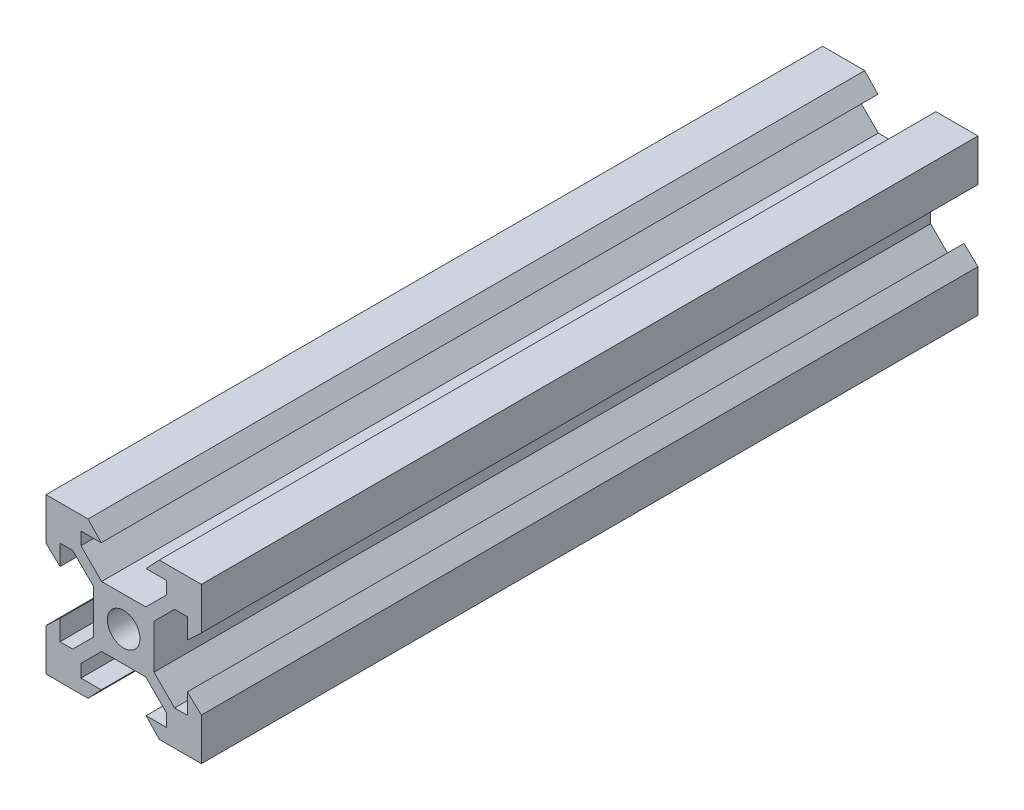
SolidWorks part; units mm, degrees
ref_plane "Front Plane" through (0, 0, 0) normal (0, 0, 1) x (1, 0, 0)
ref_plane "Top Plane" through (0, 0, 0) normal (0, 1, 0) x (1, 0, 0)
ref_plane "Right Plane" through (0, 0, 0) normal (1, 0, 0) x (0, 0, -1)
sketch "Sketch1" plane through (0, 0, 0) normal (0, 0, 1) x (1, 0, 0)
  line L0 (-4.58, 10) -> (-2.885, 8.2)
  line L1 (10, -10) -> (4.58, -10)
  line L2 (10, -10) -> (10, -4.58)
  line L3 (10, 10) -> (4.58, 10)
  line L4 (-10, -10) -> (-10, -4.58)
  line L5 (10, -10) -> (-10, 10) construction
  line L6 (10, 10) -> (-10, -10) construction
  line L7 (-2.8393, 3.9) -> (2.8393, 3.9)
  line L8 (-3.9, 2.8393) -> (-3.9, -2.8393)
  line L9 (-2.8393, -3.9) -> (2.8393, -3.9)
  line L10 (3.9, 2.8393) -> (3.9, -2.8393)
  line L11 (-3.9, 3.9) -> (3.9, -3.9) construction
  line L12 (-3.9, -3.9) -> (3.9, 3.9) construction
  line L13 (4.58, 10) -> (2.885, 8.2)
  line L14 (10, 4.58) -> (10, 10)
  line L15 (-5.5, 8.2) -> (-2.885, 8.2)
  line L16 (-8.2, 5.5) -> (-8.2, 2.885)
  line L17 (-5.5, -8.2) -> (-2.885, -8.2)
  line L18 (8.2, 5.5) -> (8.2, 2.885)
  line L19 (-8.2, 8.2) -> (8.2, -8.2) construction
  line L20 (-8.2, -8.2) -> (8.2, 8.2) construction
  line L21 (10, 4.58) -> (8.2, 2.885)
  line L22 (10, -4.58) -> (8.2, -2.885)
  line L23 (4.58, -10) -> (2.885, -8.2)
  line L24 (-4.58, -10) -> (-2.885, -8.2)
  line L25 (-10, -4.58) -> (-8.2, -2.885)
  line L26 (-10, 4.58) -> (-8.2, 2.885)
  line L27 (0, 14.7958) -> (0, -12.2524) construction
  line L28 (-5.5, 8.2) -> (-5.5, 6.5607)
  line L29 (5.5, 8.2) -> (5.5, 6.5607)
  line L30 (-5.5, 6.5607) -> (-2.8393, 3.9)
  line L31 (2.8393, 3.9) -> (5.5, 6.5607)
  line L32 (-4.58, 10) -> (-10, 10)
  line L33 (2.885, 8.2) -> (5.5, 8.2)
  line L34 (8.2, -2.885) -> (8.2, -5.5)
  line L35 (2.885, -8.2) -> (5.5, -8.2)
  line L36 (-4.58, -10) -> (-10, -10)
  line L37 (-8.2, -2.885) -> (-8.2, -5.5)
  line L38 (-10, 4.58) -> (-10, 10)
  line L39 (8.2, 5.5) -> (6.5607, 5.5)
  line L40 (6.5607, 5.5) -> (3.9, 2.8393)
  line L41 (3.9, -2.8393) -> (6.5607, -5.5)
  line L42 (8.2, -5.5) -> (6.5607, -5.5)
  line L43 (5.5, -8.2) -> (5.5, -6.5607)
  line L44 (5.5, -6.5607) -> (2.8393, -3.9)
  line L45 (-2.8393, -3.9) -> (-5.5, -6.5607)
  line L46 (-5.5, -8.2) -> (-5.5, -6.5607)
  line L47 (-8.2, -5.5) -> (-6.5607, -5.5)
  line L48 (-6.5607, -5.5) -> (-3.9, -2.8393)
  line L49 (-3.9, 2.8393) -> (-6.5607, 5.5)
  line L50 (-8.2, 5.5) -> (-6.5607, 5.5)
  circle A0 centre (0, 0) radius 2.1
  point P0 (0, 0)
  point P35 (0, 0)
  point P62 (0, 0)
  dimension "D3" = 4.2
  dimension "D1" = 20
  dimension "D4" = 9.16
  dimension "D5" = 9.16
  dimension "D6" = 1.8
  dimension "D7" = 6.1
  dimension "D8" = 5.77
  dimension "D10" = 5.5
  dimension "D11" = 5.5
  dimension "D12" = 1.5
  dimension "D13" = 1.5
  dimension "D14" = 5.77
  dimension "D15" = 20
  dimension "D9" = 4
extrude "Boss-Extrude1" add sketch "Sketch1" along normal blind 100
